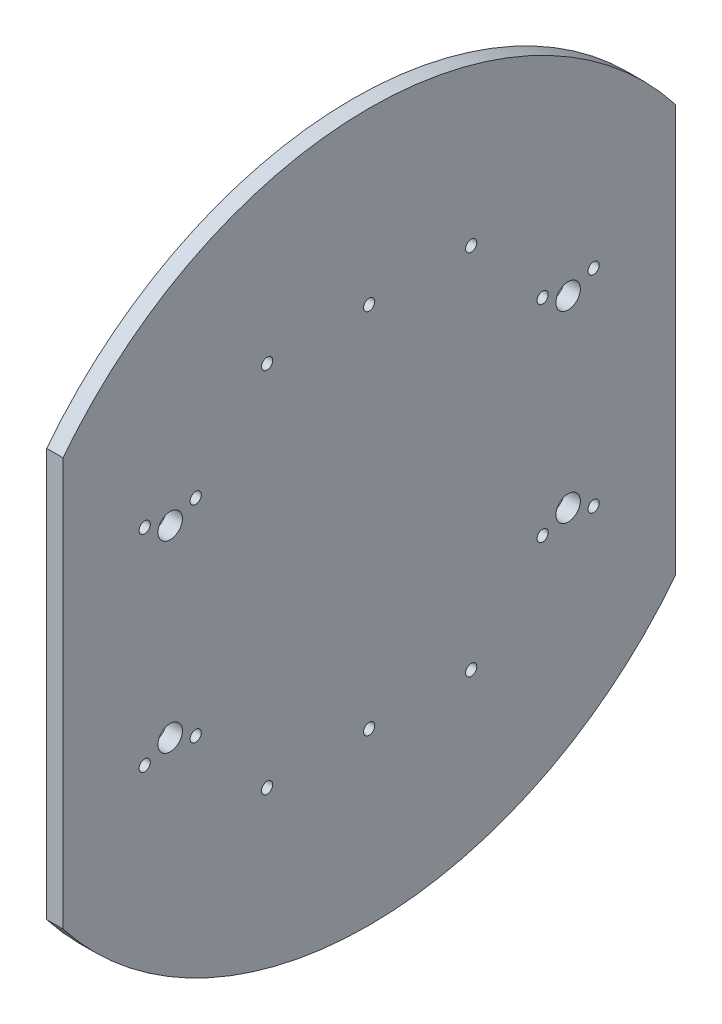
SolidWorks part; units mm, degrees
ref_plane "前视基准面" through (0, 0, 0) normal (0, 0, 1) x (1, 0, 0)
ref_plane "上视基准面" through (0, 0, 0) normal (0, 1, 0) x (1, 0, 0)
ref_plane "右视基准面" through (0, 0, 0) normal (1, 0, 0) x (0, 0, -1)
other "Configuration Table"
sketch "草图1" plane through (0, 0, 0) normal (1, 0, 0) x (0, 0, -1)
  line L0 (0, 0) -> (50000, 0) construction
  line L2 (-150, 100) -> (-150, -100)
  line L4 (150, 100) -> (150, -100)
  arc A0 (150, 100) -> (-150, 100) centre (0, -16.619) ccw
  arc A1 (150, -100) -> (-150, -100) centre (0, 16.619) cw
  point P9 (0, 0)
  dimension "D1" = 150
  dimension "D4" = 190
  dimension "D2" = 200
  dimension "D5" = 300
extrude "凸台-拉伸1" add sketch "草图1" along normal blind 8
sketch "草图2" plane through (8, 0, 0) normal (1, 0, 0) x (0, 0, -1)
  line L0 (97.5, 45) -> (97.5, -45) construction
  line L1 (0, 0) -> (0, 50000) construction
  line L2 (85, 50.5) -> (110, 50.5) construction
  line L3 (85, 50.5) -> (85, -50.5) construction
  line L4 (85, -50.5) -> (110, -50.5) construction
  line L5 (110, 50.5) -> (110, -50.5) construction
  line L6 (-110, 50.5) -> (-110, -50.5) construction
  line L7 (-85, -50.5) -> (-110, -50.5) construction
  line L8 (-85, 50.5) -> (-85, -50.5) construction
  line L9 (-85, 50.5) -> (-110, 50.5) construction
  line L10 (-97.5, 45) -> (-97.5, -45) construction
  circle A0 centre (97.5, 45) radius 6
  circle A1 centre (97.5, -45) radius 6
  circle A2 centre (85, 50.5) radius 2.75
  circle A3 centre (110, 50.5) radius 2.75
  circle A4 centre (85, -50.5) radius 2.75
  circle A5 centre (110, -50.5) radius 2.75
  circle A6 centre (-110, -50.5) radius 2.75
  circle A7 centre (-85, -50.5) radius 2.75
  circle A8 centre (-110, 50.5) radius 2.75
  circle A9 centre (-85, 50.5) radius 2.75
  circle A10 centre (-97.5, -45) radius 6
  circle A11 centre (-97.5, 45) radius 6
  point P9 (97.5, 0)
  dimension "D4" = 12
  dimension "D5" = 12
  dimension "D10" = 5.5
  dimension "D1" = 90
  dimension "D2" = 97.5
  dimension "D3" = 45
  dimension "D6" = 25
  dimension "D7" = 12.5
  dimension "D8" = 101
  dimension "D9" = 50.5
extrude "切除-拉伸1" cut sketch "草图2" against normal blind 8
sketch "草图3" plane through (8, 0, 0) normal (1, 0, 0) x (0, 0, -1)
  line L1 (-50, 90) -> (50, 90) construction
  line L2 (-50, 90) -> (-50, -90) construction
  line L3 (-50, -90) -> (50, -90) construction
  line L4 (50, 90) -> (50, -90) construction
  circle A0 centre (-50, 90) radius 2.75
  circle A1 centre (0, 90) radius 2.75
  circle A2 centre (50, 90) radius 2.75
  circle A3 centre (50, -90) radius 2.75
  circle A4 centre (0, -90) radius 2.75
  circle A5 centre (-50, -90) radius 2.75
  dimension "D5" = 5.5
  dimension "D1" = 180
  dimension "D2" = 100
  dimension "D3" = 90
  dimension "D4" = 50
extrude "切除-拉伸2" cut sketch "草图3" against normal blind 10
